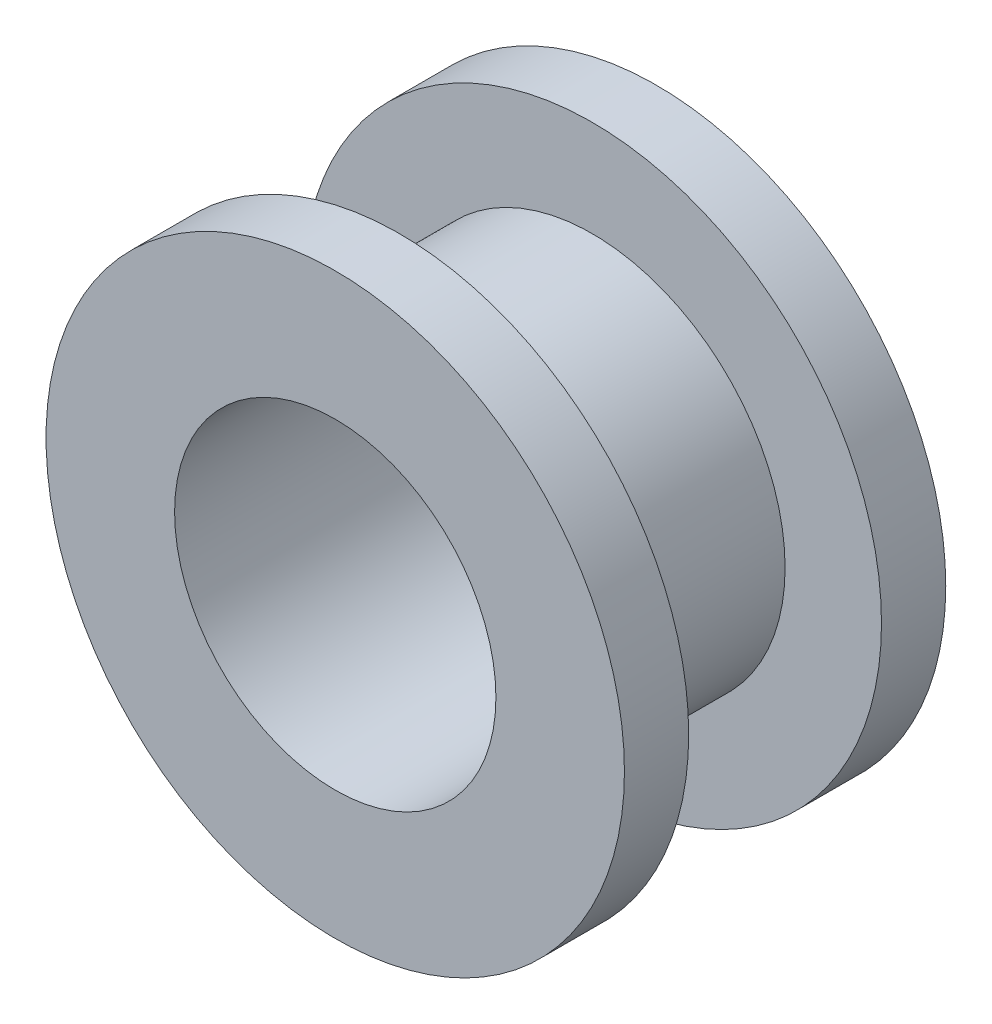
SolidWorks part; units mm, degrees
ref_plane "前视基准面" through (0, 0, 0) normal (0, 0, 1) x (1, 0, 0)
ref_plane "上视基准面" through (0, 0, 0) normal (0, 1, 0) x (1, 0, 0)
ref_plane "右视基准面" through (0, 0, 0) normal (1, 0, 0) x (0, 0, -1)
sketch "草图1" plane through (0, 0, 0) normal (0, 0, 1) x (1, 0, 0)
  circle A0 centre (0, 118.25) radius 9
  circle A1 centre (0, 118.25) radius 5
  dimension "D1" = 10
  dimension "D2" = 18
extrude "凸台-拉伸1" add sketch "草图1" along normal blind 2
sketch "草图2" plane through (0, 0, 2) normal (0, 0, 1) x (1, 0, 0)
  circle A0 centre (0, 118.25) radius 5
  circle A1 centre (0, 118.25) radius 6
  dimension "D1" = 12
extrude "凸台-拉伸2" add sketch "草图2" along normal up to surface (8 mm away)
sketch "草图3" plane through (0, 0, 10) normal (0, 0, 1) x (1, 0, 0)
  circle A0 centre (0, 118.25) radius 5
  circle A1 centre (0, 118.25) radius 9
extrude "凸台-拉伸3" add sketch "草图3" against normal blind 2
